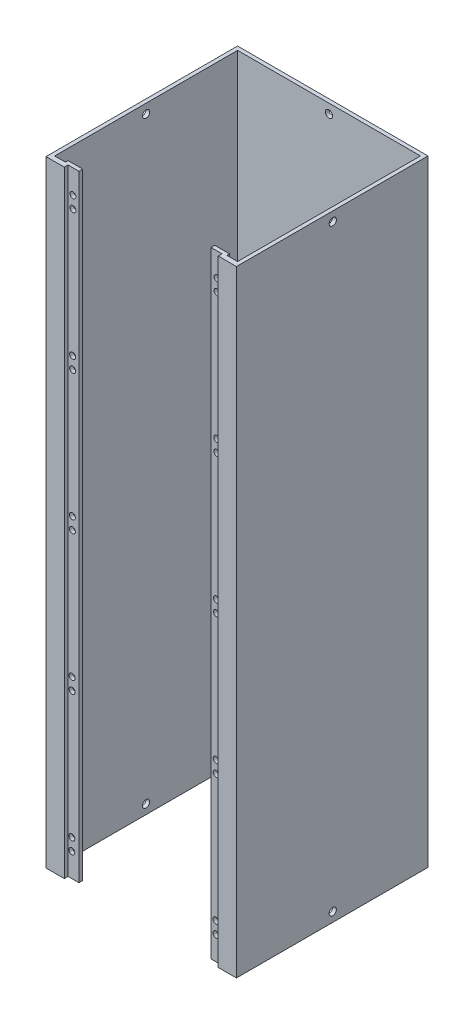
SolidWorks part; units mm, degrees
ref_plane "Front Plane" through (0, 0, 0) normal (0, 0, 1) x (1, 0, 0)
ref_plane "Top Plane" through (0, 0, 0) normal (0, 1, 0) x (1, 0, 0)
ref_plane "Right Plane" through (0, 0, 0) normal (1, 0, 0) x (0, 0, -1)
sketch "Sketch1" plane through (0, 0, 0) normal (0, 1, 0) x (1, 0, 0)
  line L0 (0, -0.603) -> (0, 101.206)
  line L1 (0, 101.206) -> (101.206, 101.206)
  line L2 (101.206, 101.206) -> (101.206, -0.6)
  line L3 (101.206, -0.6) -> (91.5, -0.6)
  line L4 (91.5, -0.6) -> (91.5, 1.4)
  line L5 (91.5, 1.4) -> (85.703, 1.4)
  line L6 (85.703, 1.4) -> (85.703, 3.4)
  line L7 (85.703, 3.4) -> (93.5, 3.4)
  line L8 (93.5, 3.4) -> (93.5, 2)
  line L9 (93.5, 2) -> (99.206, 2)
  line L10 (99.206, 2) -> (99.206, 99.206)
  line L11 (99.206, 99.206) -> (2, 99.206)
  line L12 (2, 99.206) -> (2, 2)
  line L13 (2, 2) -> (7.706, 2)
  line L14 (7.706, 2) -> (7.706, 3.397)
  line L15 (7.706, 3.397) -> (15.503, 3.397)
  line L16 (15.503, 3.397) -> (15.503, 1.397)
  line L17 (15.503, 1.397) -> (9.706, 1.397)
  line L18 (9.706, 1.397) -> (9.706, -0.603)
  line L19 (9.706, -0.603) -> (0, -0.603)
  dimension "D1" = 90
  dimension "D2" = 2
  dimension "D3" = 2
  dimension "D4" = 2
  dimension "D5" = 2
  dimension "D6" = 2
  dimension "D7" = 9.706
  dimension "D8" = 2
  dimension "D9" = 2
  dimension "D10" = 9.706
  dimension "D11" = 2
extrude "Boss-Extrude1" add sketch "Sketch1" along normal blind 327.5
sketch "Sketch2" plane through (0, 0, -1.397) normal (0, 0, 1) x (1, 0, 0)
  line L0 (9.706, 327.5) -> (15.503, 327.5) construction
  line L1 (15.503, 327.5) -> (15.503, 0) construction
  line L2 (85.703, 327.5) -> (85.703, 0) construction
  line L3 (85.703, 327.5) -> (91.5, 327.5) construction
  line L4 (9.706, 0) -> (15.503, 0) construction
  circle A0 centre (12.303, 314.9) radius 1.6
  circle A1 centre (12.303, 308.5) radius 1.6
  circle A2 centre (88.903, 314.9) radius 1.6
  circle A3 centre (88.903, 308.5) radius 1.6
  circle A4 centre (12.1523, 240.925) radius 1.6
  circle A5 centre (12.1523, 234.525) radius 1.6
  circle A6 centre (88.7523, 240.925) radius 1.6
  circle A7 centre (88.7523, 234.525) radius 1.6
  circle A8 centre (12.0015, 166.95) radius 1.6
  circle A9 centre (12.0015, 160.55) radius 1.6
  circle A10 centre (88.6015, 166.95) radius 1.6
  circle A11 centre (88.6015, 160.55) radius 1.6
  circle A12 centre (11.8508, 92.975) radius 1.6
  circle A13 centre (11.8508, 86.575) radius 1.6
  circle A14 centre (88.4508, 92.975) radius 1.6
  circle A15 centre (88.4508, 86.575) radius 1.6
  circle A16 centre (11.7, 19) radius 1.6
  circle A17 centre (11.7, 12.6) radius 1.6
  circle A18 centre (88.3, 19) radius 1.6
  circle A19 centre (88.3, 12.6) radius 1.6
  dimension "D1" = 3.2
  dimension "D2" = 3.2
  dimension "D3" = 12.6
  dimension "D4" = 6.4
  dimension "D5" = 3.2
  dimension "D6" = 3.2
  dimension "D8" = 3.2
  dimension "D9" = 3.2
  dimension "D10" = 12.6
  dimension "D12" = 12.6
  dimension "D7" = 2
  dimension "D11" = 5
extrude "Cut-Extrude2" cut sketch "Sketch2" against normal blind 10
sketch "Sketch3" plane through (101.206, 0, 0) normal (1, 0, 0) x (0, 0, -1)
  line L0 (-0.6, 327.5) -> (101.206, 327.5) construction
  line L3 (-0.6, 0) -> (101.206, 0) construction
  line L4 (2, 327.5) -> (2, 0) construction
  line L5 (99.206, 327.5) -> (99.206, 0) construction
  circle A0 centre (50.603, 322.524) radius 1.93
  circle A1 centre (50.603, 4.976) radius 1.93
  dimension "D1" = 3.86
  dimension "D7" = 3.86
  dimension "D2" = 4.976
  dimension "D3" = 48.603
  dimension "D4" = 48.603
  dimension "D5" = 48.603
  dimension "D6" = 4.976
  dimension "D8" = 48.603
extrude "Cut-Extrude3" cut sketch "Sketch3" against normal blind 102
sketch "Sketch4" plane through (0, 0, -101.206) normal (0, 0, -1) x (-1, 0, 0)
  line L0 (-101.206, 327.5) -> (0, 327.5) construction
  line L2 (-101.206, 0) -> (0, 0) construction
  line L3 (-2, 327.5) -> (-2, 0) construction
  line L4 (-99.206, 327.5) -> (-99.206, 0) construction
  circle A0 centre (-50.603, 322.524) radius 1.93
  circle A1 centre (-50.603, 4.976) radius 1.93
  dimension "D1" = 3.86
  dimension "D2" = 3.86
  dimension "D3" = 4.976
  dimension "D4" = 48.603
  dimension "D5" = 4.976
  dimension "D6" = 48.603
  dimension "D7" = 48.603
  dimension "D8" = 48.603
extrude "Cut-Extrude4" cut sketch "Sketch4" against normal blind 10
